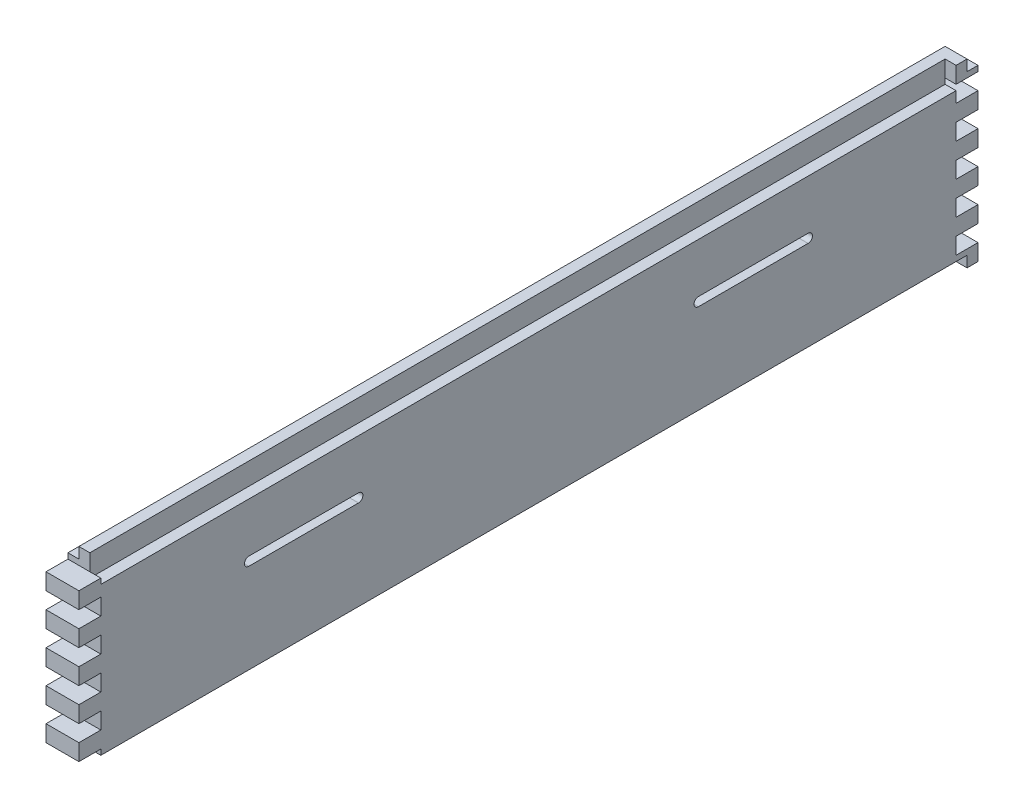
SolidWorks part; units mm, degrees
material "Сосна"
ref_plane "Спереди" through (0, 0, 0) normal (0, 0, 1) x (1, 0, 0)
ref_plane "Сверху" through (0, 0, 0) normal (0, 1, 0) x (1, 0, 0)
ref_plane "Справа" through (0, 0, 0) normal (1, 0, 0) x (0, 0, -1)
sketch "Эскиз1" plane through (0, 0, 0) normal (0, 0, 1) x (1, 0, 0)
  line L0 (0, 0) -> (0, 155)
  line L1 (0, 155) -> (10, 155)
  line L2 (10, 155) -> (10, 165)
  line L3 (10, 165) -> (20, 165)
  line L4 (20, 165) -> (20, 145)
  line L5 (20, 145) -> (30, 145)
  line L6 (30, 145) -> (30, 10)
  line L7 (30, 10) -> (10, 10)
  line L8 (10, 10) -> (10, 0)
  line L9 (10, 0) -> (0, 0)
  dimension "D1" = 10
  dimension "D2" = 10
  dimension "D3" = 10
  dimension "D4" = 10
  dimension "D5" = 20
  dimension "D6" = 10
  dimension "D7" = 10
  dimension "D8" = 155
extrude "Бобышка-Вытянуть1" add sketch "Эскиз1" along normal blind 820
sketch "Эскиз2" plane through (10, 0, 0) normal (1, 0, 0) x (0, 0, -1)
  line L0 (-820, 10) -> (0, 10) construction
  line L1 (-820, 0) -> (-810, 0)
  line L2 (-820, 0) -> (-820, 10)
  line L3 (-820, 10) -> (-810, 10)
  line L4 (-810, 0) -> (-810, 10)
  line L5 (-410, 0) -> (-410, 171.2653) construction
  line L6 (-820, 0) -> (0, 0) construction
  line L7 (-10, 0) -> (-10, 10)
  line L8 (0, 10) -> (-10, 10)
  line L9 (0, 0) -> (0, 10)
  line L10 (0, 0) -> (-10, 0)
  dimension "D1" = 10
extrude "Бобышка-Вытянуть2" add sketch "Эскиз2" along normal up to surface (20 mm away) up to face at (30, 77.5, 410)
sketch "Эскиз4" plane through (20, 0, 0) normal (1, 0, 0) x (0, 0, -1)
  line L0 (-820, 145) -> (0, 145) construction
  line L1 (-820, 165) -> (-800, 165)
  line L2 (-820, 165) -> (-820, 145)
  line L3 (-820, 145) -> (-800, 145)
  line L4 (-800, 165) -> (-800, 145)
  line L5 (-410, 165) -> (-410, 0) construction
  line L6 (-820, 165) -> (0, 165) construction
  line L7 (-20, 165) -> (-20, 145)
  line L8 (0, 145) -> (-20, 145)
  line L9 (0, 165) -> (0, 145)
  line L10 (0, 165) -> (-20, 165)
  dimension "D1" = 20
extrude "Бобышка-Вытянуть3" add sketch "Эскиз4" along normal up to surface (10 mm away) up to face at (30, 38.75, 410)
sketch "Эскиз5" plane through (30, 0, 0) normal (1, 0, 0) x (0, 0, -1)
  line L0 (-410, 145) -> (-410, 0) construction
  line L1 (-820, 165) -> (-810, 165)
  line L2 (-820, 165) -> (-820, 155)
  line L3 (-820, 155) -> (-810, 155)
  line L4 (-810, 165) -> (-810, 155)
  line L5 (-800, 145) -> (-20, 145) construction
  line L6 (-10, 165) -> (-10, 155)
  line L7 (0, 155) -> (-10, 155)
  line L8 (0, 165) -> (0, 155)
  line L9 (0, 165) -> (-10, 165)
  dimension "D1" = 10
  dimension "D2" = 10
extrude "Вырез-Вытянуть2" cut sketch "Эскиз5" against normal through all
sketch "Эскиз6" plane through (30, 0, 0) normal (1, 0, 0) x (0, 0, -1)
  line L0 (-155, 91.8465) -> (-255, 91.8465)
  line L1 (-155, 99.8465) -> (-255, 99.8465)
  line L2 (-410, 10) -> (-410, 145) construction
  line L3 (-810, 10) -> (-10, 10) construction
  line L4 (-800, 145) -> (-20, 145) construction
  line L6 (-665, 99.8465) -> (-565, 99.8465)
  line L8 (-665, 91.8465) -> (-565, 91.8465)
  arc A0 (-665, 91.8465) -> (-665, 99.8465) centre (-665, 95.8465) cw
  arc A1 (-565, 91.8465) -> (-565, 99.8465) centre (-565, 95.8465) ccw
  arc A2 (-255, 91.8465) -> (-255, 99.8465) centre (-255, 95.8465) cw
  arc A3 (-155, 91.8465) -> (-155, 99.8465) centre (-155, 95.8465) ccw
  dimension "D1" = 8
  dimension "D2" = 100
extrude "Вырез-Вытянуть3" cut sketch "Эскиз6" against normal through all
sketch "Эскиз7" plane through (0, 0, 0) normal (-1, 0, 0) x (0, 0, 1)
  line L1 (820, 0) -> (800, 0)
  line L2 (820, 0) -> (820, 15)
  line L3 (820, 15) -> (800, 15)
  line L4 (800, 0) -> (800, 15)
  dimension "D1" = 15
  dimension "D2" = 20
extrude "Вырез-Вытянуть4" cut sketch "Эскиз7" against normal through all
pattern_linear "Линейный массив1" count 1 spacing 10 along (0, 0, -1) count 6 spacing 30 along (0, 1, 0) of "Вырез-Вытянуть4"
sketch "Эскиз8" plane through (0, 0, 0) normal (-1, 0, 0) x (0, 0, 1)
  line L0 (0, 155) -> (0, 0) construction
  line L1 (0, 30) -> (20, 30)
  line L2 (0, 30) -> (0, 15)
  line L3 (0, 15) -> (20, 15)
  line L4 (20, 30) -> (20, 15)
  line L5 (800, 0) -> (0, 0) construction
  dimension "D1" = 20
  dimension "D2" = 15
  dimension "D3" = 15
extrude "Вырез-Вытянуть5" cut sketch "Эскиз8" against normal through all
pattern_linear "Линейный массив2" count 1 spacing 10 along (0, 0, 1) count 5 spacing 30 along (0, 1, 0) of "Вырез-Вытянуть5"
